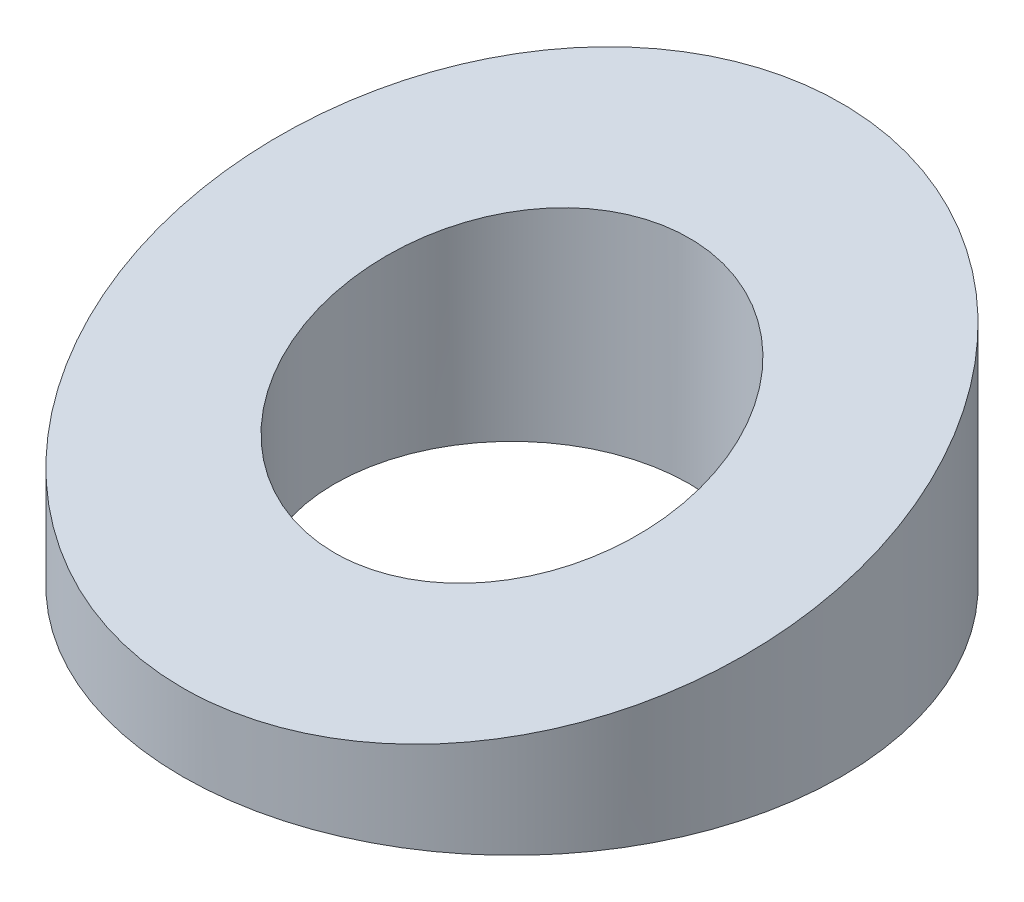
SolidWorks part; units mm, degrees
ref_plane "Front Plane" through (0, 0, 0) normal (0, 0, 1) x (1, 0, 0)
ref_plane "Top Plane" through (0, 0, 0) normal (0, 1, 0) x (1, 0, 0)
ref_plane "Right Plane" through (0, 0, 0) normal (1, 0, 0) x (0, 0, -1)
sketch "Sketch1" plane through (0, 0, 0) normal (0, 1, 0) x (1, 0, 0)
  circle A0 centre (0, 0) radius 3.5
  circle A1 centre (0, 0) radius 6.5
  dimension "D1" = 7
  dimension "D2" = 3
extrude "Boss-Extrude1" add sketch "Sketch1" along normal blind 5
sketch "Sketch2" plane through (0, 0, 0) normal (1, 0, 0) x (0, 0, -1)
  line L0 (6.5, 5) -> (-6.5, 1.5167)
  line L1 (-6.5, 5) -> (-6.5, 0) construction
  line L2 (6.5, 5) -> (-6.5, 5) construction
  line L4 (-6.5, 1.5167) -> (6.5, 1.5167)
  line L5 (-6.5, 1.5167) -> (-6.5, 5)
  line L6 (-6.5, 5) -> (6.5, 5)
  line L7 (6.5, 1.5167) -> (6.5, 5)
  dimension "D1" = 15
extrude "Cut-Extrude1" cut sketch "Sketch2" against normal blind 10 and the other way blind 10 contours L6 L5 L0
